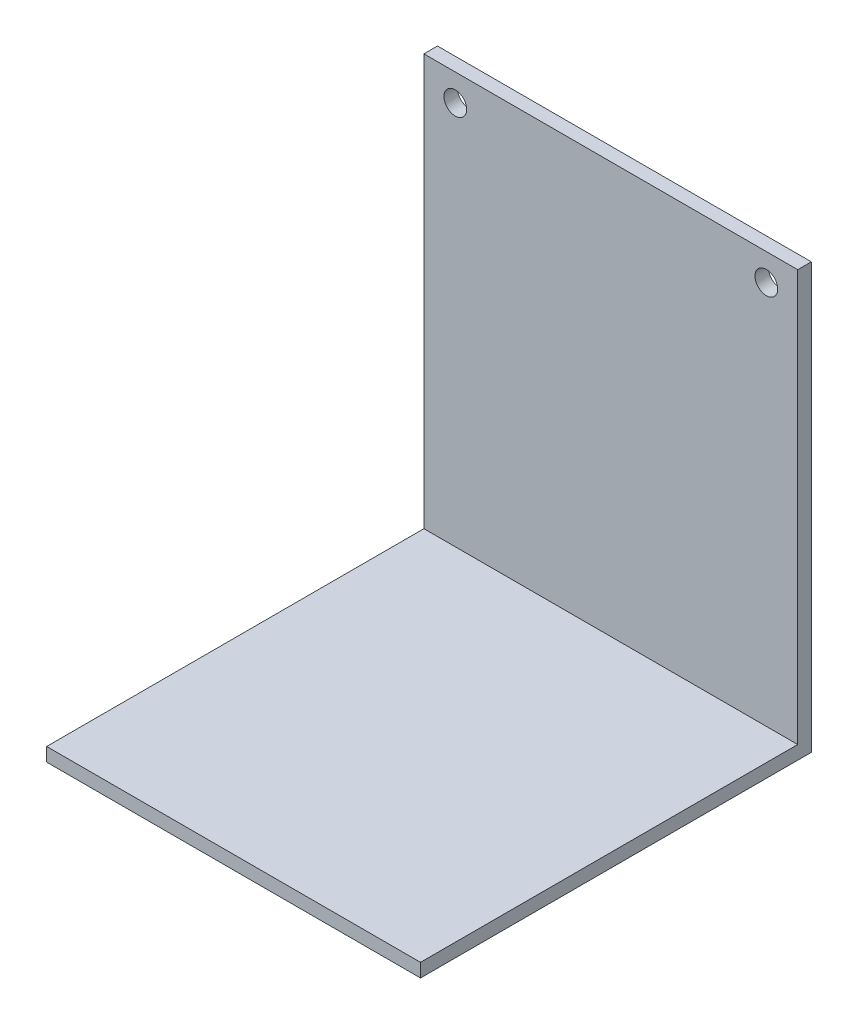
SolidWorks part; units mm, degrees
material "6061 Alloy"
ref_plane "Front Plane" through (0, 0, 0) normal (0, 0, 1) x (1, 0, 0)
ref_plane "Top Plane" through (0, 0, 0) normal (0, 1, 0) x (1, 0, 0)
ref_plane "Right Plane" through (0, 0, 0) normal (1, 0, 0) x (0, 0, -1)
sketch "Sketch1" plane through (0, 0, 0) normal (0, 0, 1) x (1, 0, 0)
  line L1 (-111.6772, -83.4473) -> (-41.8272, -83.4473)
  line L2 (-111.6772, -83.4473) -> (-111.6772, -4.0723)
  line L3 (-111.6772, -4.0723) -> (-41.8272, -4.0723)
  line L4 (-41.8272, -83.4473) -> (-41.8272, -4.0723)
  dimension "D1" = 69.85
  dimension "D2" = 79.375
extrude "Boss-Extrude1" add sketch "Sketch1" along normal blind 73.025
sketch "Sketch3" plane through (-41.8272, 0, 0) normal (1, 0, 0) x (0, 0, -1)
  line L0 (0, -83.4473) -> (0, -4.0723) construction
  line L1 (-111.8253, -80.9073) -> (-2.54, -80.9073)
  line L2 (-111.8253, -80.9073) -> (-111.8253, 1.0924)
  line L3 (-111.8253, 1.0924) -> (-2.54, 1.0924)
  line L4 (-2.54, -80.9073) -> (-2.54, 1.0924)
  line L5 (-111.8253, -80.9073) -> (-2.54, 1.0924) construction
  line L6 (-111.8253, 1.0924) -> (-2.54, -80.9073) construction
  line L7 (-73.025, -83.4473) -> (0, -83.4473) construction
  point P0 (-57.1826, -39.9074)
  dimension "D1" = 2.54
  dimension "D2" = 2.54
extrude "Cut-Extrude1" cut sketch "Sketch3" against normal through all
sketch "Sketch4" plane through (0, 0, 0) normal (0, 0, -1) x (-1, 0, 0)
  line L0 (41.8272, -83.4473) -> (41.8272, -4.0723) construction
  line L1 (111.6772, -4.0723) -> (111.6772, -83.4473) construction
  circle A0 centre (47.6946, -9.0901) radius 2.1239
  circle A1 centre (105.8098, -9.0901) radius 2.1239
  dimension "D2" = 5.8674
  dimension "D3" = 5.8674
  dimension "D1" = 2
extrude "Cut-Extrude2" cut sketch "Sketch4" against normal through all
